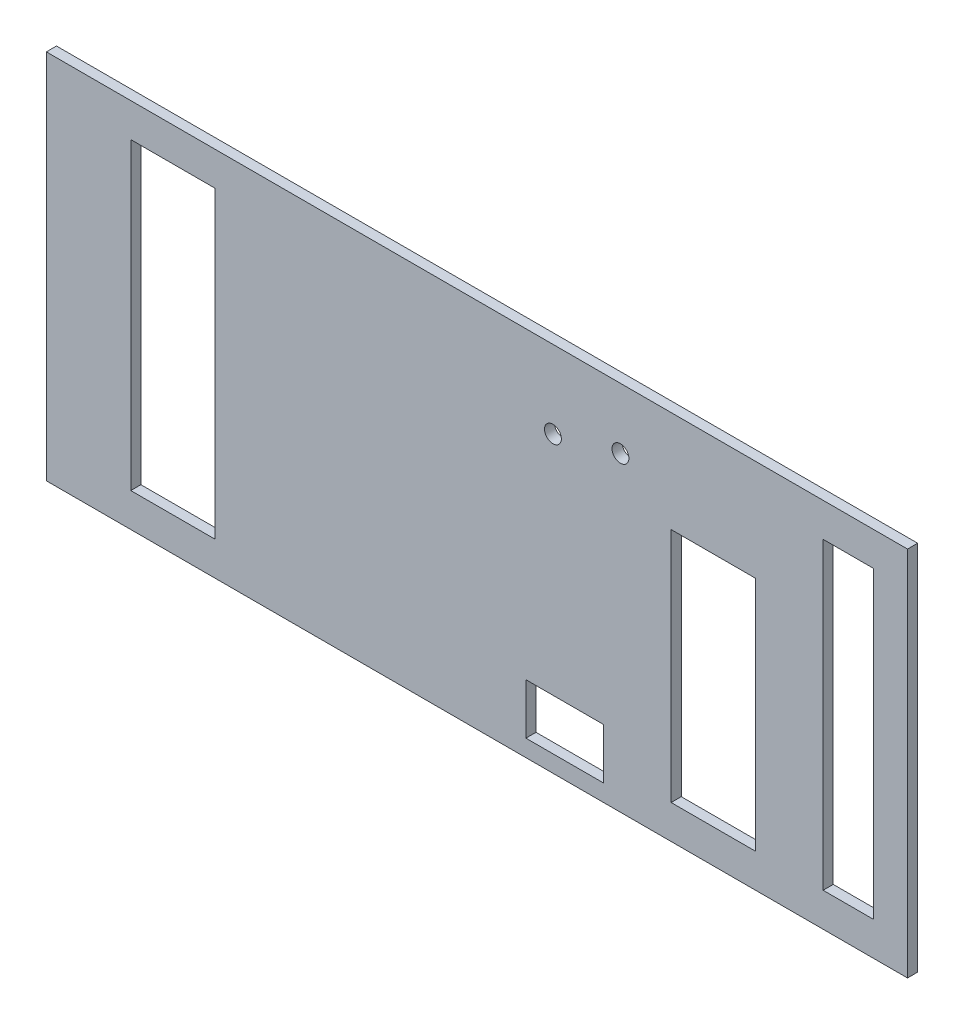
SolidWorks part; units mm, degrees
ref_plane "Front Plane" through (0, 0, 0) normal (0, 0, 1) x (1, 0, 0)
ref_plane "Top Plane" through (0, 0, 0) normal (0, 1, 0) x (1, 0, 0)
ref_plane "Right Plane" through (0, 0, 0) normal (1, 0, 0) x (0, 0, -1)
sketch "Sketch1" plane through (0, 0, 0) normal (0, 0, 1) x (1, 0, 0)
  line L0 (-120.7261, -7.2607) -> (134.2739, -7.2607) construction
  line L1 (-120.7261, 47.7393) -> (134.2739, 47.7393)
  line L2 (-120.7261, 47.7393) -> (-120.7261, -62.2607)
  line L3 (-120.7261, -62.2607) -> (134.2739, -62.2607)
  line L4 (134.2739, 47.7393) -> (134.2739, -62.2607)
  line L5 (109.2739, 37.7393) -> (124.2739, 37.7393)
  line L6 (109.2739, 37.7393) -> (109.2739, -52.2607)
  line L7 (109.2739, -52.2607) -> (124.2739, -52.2607)
  line L8 (124.2739, 37.7393) -> (124.2739, -52.2607)
  line L10 (-95.7261, 37.7393) -> (-70.7261, 37.7393)
  line L11 (-95.7261, 37.7393) -> (-95.7261, -52.2607)
  line L12 (-95.7261, -52.2607) -> (-70.7261, -52.2607)
  line L13 (-70.7261, 37.7393) -> (-70.7261, -52.2607)
  line L14 (21.2739, -42.2607) -> (44.2739, -42.2607)
  line L15 (21.2739, -42.2607) -> (21.2739, -57.2607)
  line L16 (21.2739, -57.2607) -> (44.2739, -57.2607)
  line L17 (44.2739, -42.2607) -> (44.2739, -57.2607)
  line L18 (64.2739, 17.7393) -> (89.2739, 17.7393)
  line L19 (64.2739, 17.7393) -> (64.2739, -52.2607)
  line L20 (64.2739, -52.2607) -> (89.2739, -52.2607)
  line L21 (89.2739, 17.7393) -> (89.2739, -52.2607)
  circle A0 centre (29.2739, 24.7393) radius 2.5
  circle A1 centre (49.2739, 29.7393) radius 2.5
  point P10 (116.7739, 37.7393)
  dimension "D20" = 5
  dimension "D22" = 5
  dimension "D1" = 110
  dimension "D2" = 255
  dimension "D3" = 230
  dimension "D4" = 245
  dimension "D5" = 90
  dimension "D6" = 45
  dimension "D7" = 90
  dimension "D8" = 45
  dimension "D9" = 165
  dimension "D10" = 5
  dimension "D11" = 20
  dimension "D12" = 142
  dimension "D13" = 25
  dimension "D14" = 50
  dimension "D15" = 185
  dimension "D16" = 210
  dimension "D17" = 70
  dimension "D18" = 10
  dimension "D19" = 150
  dimension "D21" = 170
  dimension "D23" = 87
  dimension "D24" = 92
extrude "Boss-Extrude1" add sketch "Sketch1" along normal blind 3
